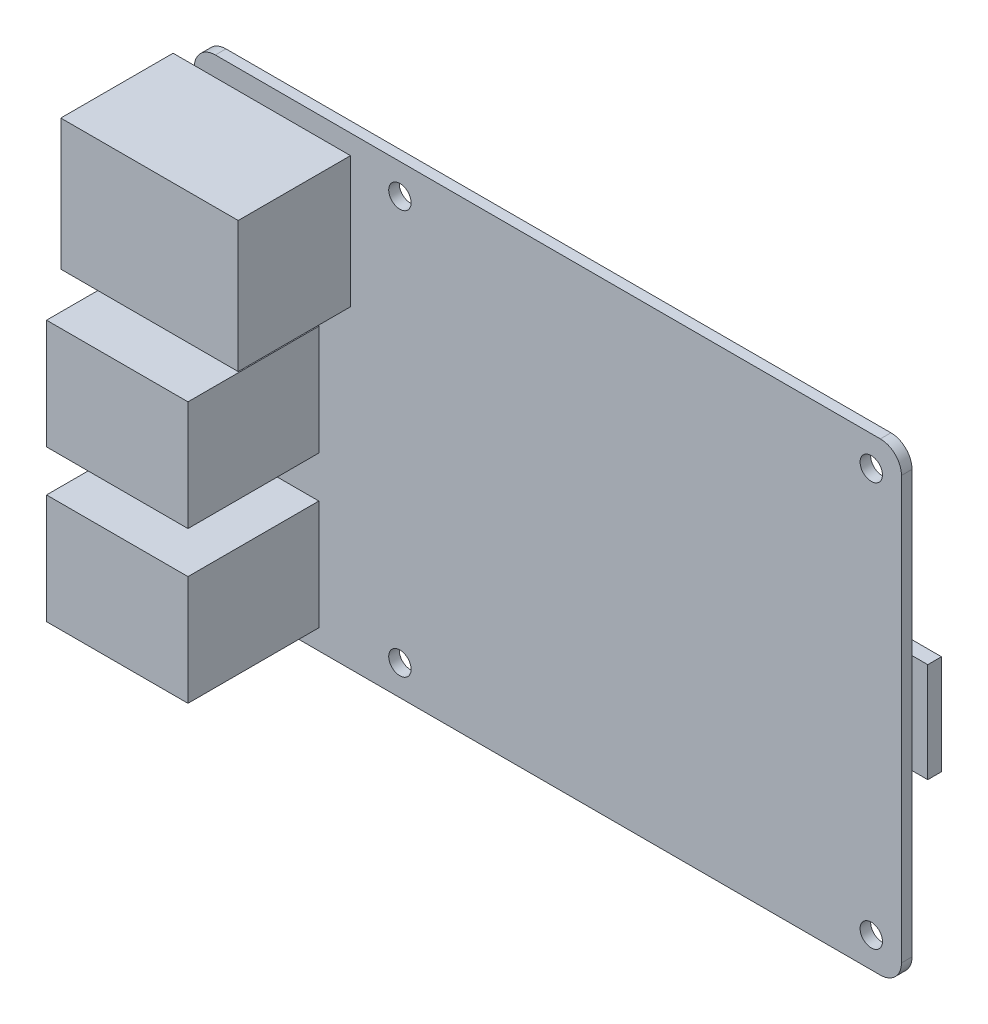
SolidWorks part; units mm, degrees
ref_plane "Front Plane" through (0, 0, 0) normal (0, 0, 1) x (1, 0, 0)
ref_plane "Top Plane" through (0, 0, 0) normal (0, 1, 0) x (1, 0, 0)
ref_plane "Right Plane" through (0, 0, 0) normal (1, 0, 0) x (0, 0, -1)
sketch "Sketch1" plane through (0, 0, 0) normal (0, 0, 1) x (1, 0, 0)
  line L1 (85.09, 0) -> (0, 0)
  line L2 (85.09, 0) -> (85.09, 55.88)
  line L3 (85.09, 55.88) -> (0, 55.88)
  line L4 (0, 0) -> (0, 55.88)
  dimension "D1" = 85.09
  dimension "D2" = 55.88
extrude "Boss-Extrude1" add sketch "Sketch1" along normal blind 1.27
fillet "Fillet2" radius 2.54 4 edges at (0, 0, 0.635) (85.09, 0, 0.635) (85.09, 55.88, 0.635) (0, 55.88, 0.635)
sketch "Sketch2" plane through (0, 0, 1.27) normal (0, 0, 1) x (1, 0, 0)
  line L0 (85.09, 2.54) -> (85.09, 53.34) construction
  line L1 (24.7396, 52.2478) -> (81.4578, 52.2478) construction
  line L2 (24.7396, 52.2478) -> (24.7396, 3.6322) construction
  line L3 (24.7396, 3.6322) -> (81.4578, 3.6322) construction
  line L4 (81.4578, 52.2478) -> (81.4578, 3.6322) construction
  line L5 (24.7396, 27.94) -> (81.4578, 27.94) construction
  line L6 (81.4578, 27.94) -> (85.09, 27.94) construction
  line L7 (81.4578, 3.6322) -> (81.4578, 0) construction
  line L9 (2.54, 0) -> (82.55, 0) construction
  circle A0 centre (81.4578, 52.2478) radius 1.3462
  circle A1 centre (24.7396, 52.2478) radius 1.3462
  circle A2 centre (24.7396, 3.6322) radius 1.3462
  circle A3 centre (81.4578, 3.6322) radius 1.3462
  point P14 (53.0987, 27.94)
  dimension "D3" = 2.6924
  dimension "D1" = 56.7182
  dimension "D2" = 3.6322
  dimension "D4" = 3.6322
extrude "Cut-Extrude1" cut sketch "Sketch2" against normal blind 1.27
sketch "Sketch3" plane through (0, 0, 1.27) normal (0, 0, 1) x (1, 0, 0)
  line L0 (6.477, 20.6248) -> (6.477, 15.621) construction
  line L1 (-2.032, 33.8328) -> (14.986, 33.8328)
  line L2 (-2.032, 33.8328) -> (-2.032, 20.6248)
  line L3 (-2.032, 20.6248) -> (14.986, 20.6248)
  line L4 (14.986, 33.8328) -> (14.986, 20.6248)
  line L5 (-2.032, 15.621) -> (14.986, 15.621)
  line L6 (-2.032, 15.621) -> (-2.032, 2.413)
  line L7 (-2.032, 2.413) -> (14.986, 2.413)
  line L8 (14.986, 15.621) -> (14.986, 2.413)
  line L9 (0, 53.34) -> (0, 2.54) construction
  line L10 (6.477, 2.413) -> (6.477, 0) construction
  line L11 (2.54, 0) -> (82.55, 0) construction
  line L12 (85.09, 2.54) -> (85.09, 53.34) construction
  line L13 (14.986, 27.2288) -> (85.09, 27.2288) construction
  point P20 (0, 0)
  dimension "D1" = 5.0038
  dimension "D2" = 2.413
  dimension "D3" = 70.104
  dimension "D4" = 13.208
  dimension "D5" = 17.018
extrude "Boss-Extrude2" add sketch "Sketch3" along normal blind 15.748
sketch "Sketch4" plane through (0, 0, 1.27) normal (0, 0, 1) x (1, 0, 0)
  line L0 (0, 53.34) -> (0, 33.8328) construction
  line L1 (-2.5527, 53.5178) -> (18.796, 53.5178)
  line L2 (-2.5527, 53.5178) -> (-2.5527, 37.7698)
  line L3 (-2.5527, 37.7698) -> (18.796, 37.7698)
  line L4 (18.796, 53.5178) -> (18.796, 37.7698)
  line L5 (8.1217, 55.88) -> (8.1217, 53.5178) construction
  line L6 (85.09, 2.54) -> (85.09, 53.34) construction
  line L7 (82.55, 55.88) -> (2.54, 55.88) construction
  line L8 (18.796, 45.6438) -> (85.09, 45.6438) construction
  line L9 (85.09, 2.54) -> (85.09, 53.34) construction
  line L10 (82.55, 55.88) -> (2.54, 55.88) construction
  dimension "D1" = 15.748
  dimension "D2" = 21.3487
  dimension "D3" = 2.3622
  dimension "D4" = 66.294
extrude "Boss-Extrude3" add sketch "Sketch4" along normal blind 13.5128
sketch "Sketch5" plane through (0, 0, 0) normal (0, 0, -1) x (-1, 0, 0)
  line L0 (-82.55, 55.88) -> (-2.54, 55.88) construction
  line L1 (-86.9823, 33.9344) -> (-71.4883, 33.9344)
  line L2 (-86.9823, 33.9344) -> (-86.9823, 21.9456)
  line L3 (-86.9823, 21.9456) -> (-71.4883, 21.9456)
  line L4 (-71.4883, 33.9344) -> (-71.4883, 21.9456)
  line L5 (-85.09, 2.54) -> (-85.09, 53.34) construction
  line L6 (-71.4883, 27.94) -> (0, 27.94) construction
  line L7 (-2.54, 0) -> (-82.55, 0) construction
  line L8 (0, 53.34) -> (0, 2.54) construction
  dimension "D1" = 11.9888
  dimension "D2" = 15.494
  dimension "D3" = 71.4883
extrude "Boss-Extrude4" add sketch "Sketch5" along normal blind 1.651
